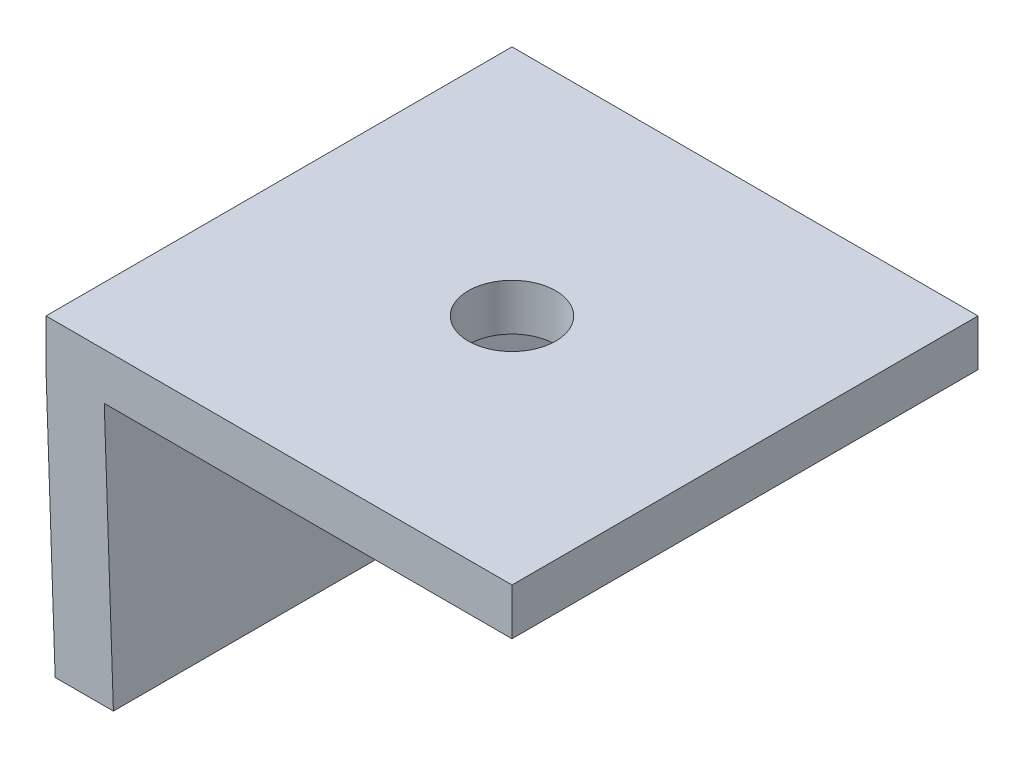
SolidWorks part; units mm, degrees
ref_plane "Front Plane" through (0, 0, 0) normal (0, 0, 1) x (1, 0, 0)
ref_plane "Top Plane" through (0, 0, 0) normal (0, 1, 0) x (1, 0, 0)
ref_plane "Right Plane" through (0, 0, 0) normal (1, 0, 0) x (0, 0, -1)
sketch "Sketch1" plane through (0, 0, 0) normal (0, 0, 1) x (1, 0, 0)
  line L0 (0, 0) -> (3.175, 0)
  line L1 (0, 0) -> (0.4986, -14.2788)
  line L2 (3.175, 0) -> (3.6736, -14.2788)
  line L3 (0.4986, -14.2788) -> (3.6736, -14.2788)
extrude "Boss-Extrude1" add sketch "Sketch1" along normal blind 25.4
sketch "Sketch2" plane through (0, 0, 0) normal (0, 1, 0) x (1, 0, 0)
  line L1 (0, 0) -> (25.4, 0)
  line L2 (0, 0) -> (0, -25.4)
  line L3 (0, -25.4) -> (25.4, -25.4)
  line L4 (25.4, 0) -> (25.4, -25.4)
  circle A0 centre (12.7, -12.7) radius 2.3813
extrude "Boss-Extrude2" add sketch "Sketch2" along normal blind 2.54
sketch "Sketch3" plane through (25.4, 0, 0) normal (1, 0, 0) x (0, 0, -1)
  circle A0 centre (-12.7, -7.1668) radius 3.175
extrude "Cut-Extrude1" cut sketch "Sketch3" against normal blind 41.148
